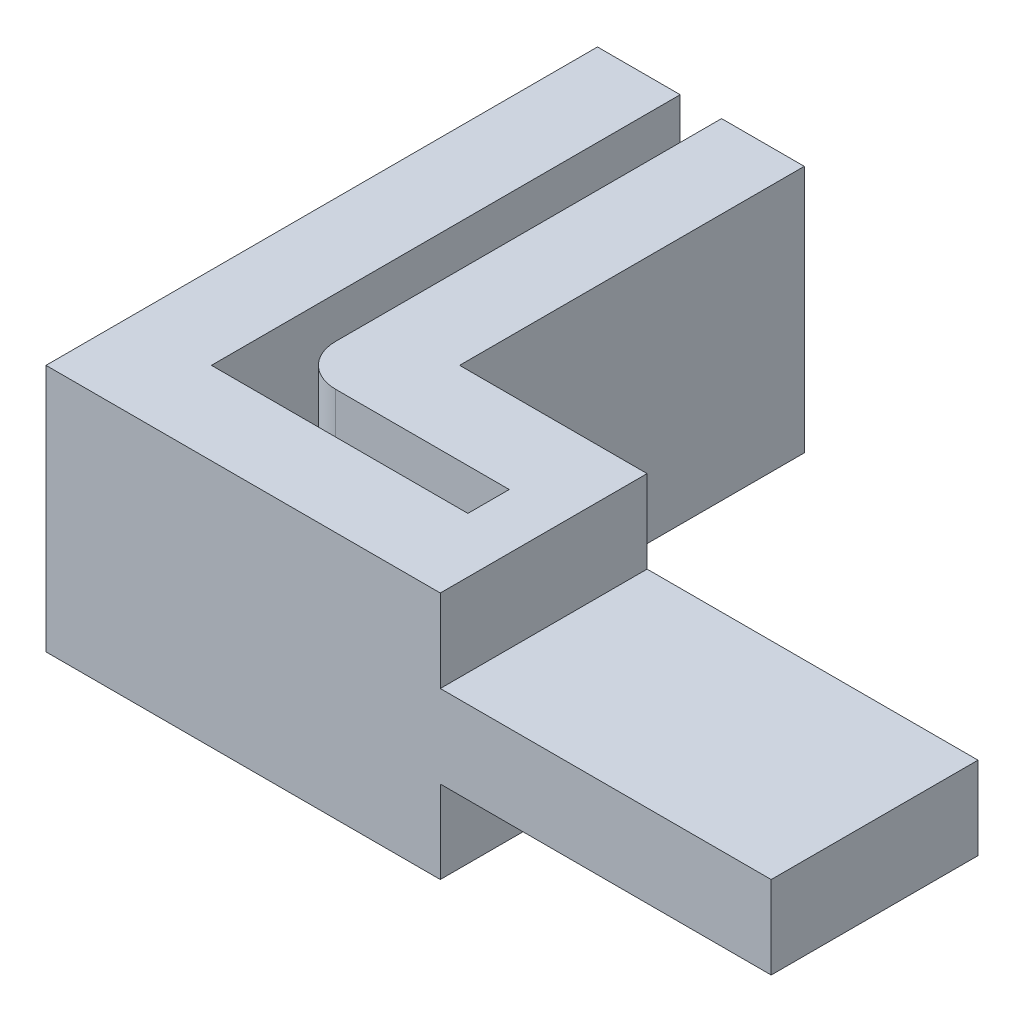
SolidWorks part; units mm, degrees
ref_plane "Front Plane" through (0, 0, 0) normal (0, 0, 1) x (1, 0, 0)
ref_plane "Top Plane" through (0, 0, 0) normal (0, 1, 0) x (1, 0, 0)
ref_plane "Right Plane" through (0, 0, 0) normal (1, 0, 0) x (0, 0, -1)
sketch "Sketch1" plane through (0, 0, 0) normal (0, 1, 0) x (1, 0, 0)
  line L1 (-5.65, -1.5) -> (5.65, -1.5)
  line L2 (-5.65, -1.5) -> (-5.65, 1.5)
  line L3 (-5.65, 1.5) -> (5.65, 1.5)
  line L4 (5.65, -1.5) -> (5.65, 1.5)
  line L5 (-5.65, -1.5) -> (5.65, 1.5) construction
  line L6 (-5.65, 1.5) -> (5.65, -1.5) construction
  line L7 (3.65, 6) -> (5.65, 6)
  line L8 (3.65, 6) -> (3.65, 1.5)
  line L9 (3.65, 1.5) -> (5.65, 1.5)
  line L10 (5.65, 6) -> (5.65, 1.5)
  line L11 (3.65, 6) -> (5.65, 1.5) construction
  line L12 (3.65, 1.5) -> (5.65, 6) construction
  line L13 (-4.15, 3) -> (3.65, 3)
  line L14 (-4.15, 3) -> (-4.15, 6)
  line L15 (-4.15, 6) -> (3.65, 6)
  line L16 (3.65, 3) -> (3.65, 6)
  line L17 (-4.15, 3) -> (3.65, 6) construction
  line L18 (-4.15, 6) -> (3.65, 3) construction
  line L19 (-8.65, 18.5) -> (-5.65, 18.5)
  line L20 (-8.65, 18.5) -> (-8.65, -1.5)
  line L21 (-8.65, -1.5) -> (-5.65, -1.5)
  line L22 (-5.65, 18.5) -> (-5.65, -1.5)
  line L23 (-8.65, 18.5) -> (-5.65, -1.5) construction
  line L24 (-8.65, -1.5) -> (-5.65, 18.5) construction
  line L25 (-1.15, 18.5) -> (-4.15, 18.5)
  line L26 (-1.15, 18.5) -> (-1.15, 6)
  line L27 (-1.15, 6) -> (-4.15, 6)
  line L28 (-4.15, 18.5) -> (-4.15, 6)
  line L29 (-1.15, 18.5) -> (-4.15, 6) construction
  line L30 (-1.15, 6) -> (-4.15, 18.5) construction
  point P0 (0, 0)
  point P6 (4.65, 3.75)
  point P7 (-0.25, 4.5)
  point P11 (-7.15, 8.5)
  point P15 (-2.65, 12.25)
  dimension "D1" = 1.5
  dimension "D2" = 1.5
  dimension "D3" = 3
  dimension "D4" = 3
  dimension "D5" = 2
  dimension "D6" = 3
  dimension "D7" = 3
  dimension "D8" = 11.3
  dimension "D9" = 20
extrude "Boss-Extrude1" add sketch "Sketch1" along normal blind 9 contours L22 L19 L20 L21 L2 | L1 L4 L3 L2 | L10 L7 L8 L3 | L15 L14 L13 L8 | L25 L28 L15 L26
fillet "Fillet1" radius 1.5 1 edges at (-4.15, 4.5, -3)
sketch "Sketch2" plane through (5.65, 0, 0) normal (1, 0, 0) x (0, 0, -1)
  line L0 (2.25, 9) -> (2.25, 0) construction
  line L1 (-1.5, 9) -> (6, 9) construction
  line L2 (-1.5, 0) -> (6, 0) construction
  line L3 (6, 9) -> (6, 0) construction
  line L4 (-1.5, 3) -> (6, 3)
  line L5 (-1.5, 3) -> (-1.5, 6)
  line L6 (-1.5, 6) -> (6, 6)
  line L7 (6, 3) -> (6, 6)
  line L8 (-1.5, 3) -> (6, 6) construction
  line L9 (-1.5, 6) -> (6, 3) construction
  point P6 (2.25, 4.5)
  dimension "D1" = 3
extrude "Boss-Extrude2" add sketch "Sketch2" along normal blind 12
